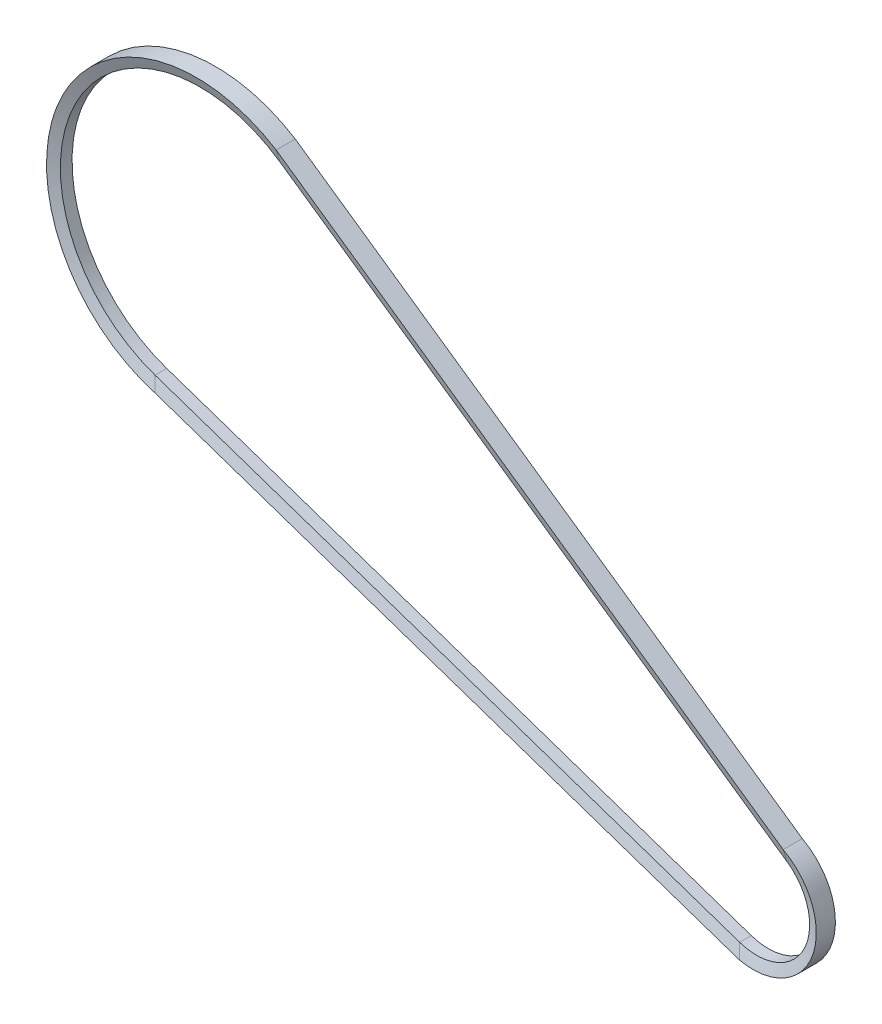
SolidWorks part; units mm, degrees
ref_plane "Front Plane" through (0, 0, 0) normal (0, 0, 1) x (1, 0, 0)
ref_plane "Top Plane" through (0, 0, 0) normal (0, 1, 0) x (1, 0, 0)
ref_plane "Right Plane" through (0, 0, 0) normal (1, 0, 0) x (0, 0, -1)
sketch "Sketch2" plane through (0, 0, 0) normal (0, 0, 1) x (1, 0, 0)
  line L0 (0, 0) -> (1, 0) construction
  line L1 (0, 0) -> (0, 1) construction
  line L2 (91.876, 132.2112) -> (676.0002, -273.7076)
  line L3 (621.5406, -381.5486) -> (-51.8615, -152.4184)
  arc A0 (-51.8615, -152.4184) -> (91.876, 132.2112) centre (0, 0) cw
  arc A1 (676.0002, -273.7076) -> (621.5406, -381.5486) centre (641.19, -323.8) cw
ref_plane "Plane1" through (91.876, 0, 0) normal (1, 0, 0) x (0, 0, -1)
sketch "Sketch3" plane through (91.876, 0, 0) normal (1, 0, 0) x (0, 0, -1)
  line L0 (-6.72, 132.2112) -> (6.72, 132.2112)
  line L1 (0, 161) -> (0, -152.4184) construction
  line L2 (6.72, 132.2112) -> (11, 146.2104)
  line L3 (11, 146.2104) -> (-11, 146.2104)
  line L4 (-11, 146.2104) -> (-6.72, 132.2112)
  dimension "D1" = 13.44
  dimension "D2" = 6.72
  dimension "D3" = 22
  dimension "D4" = 73
  dimension "D5" = 73
sweep "Sweep1" add profiles "Sketch3" path "Sketch2"
